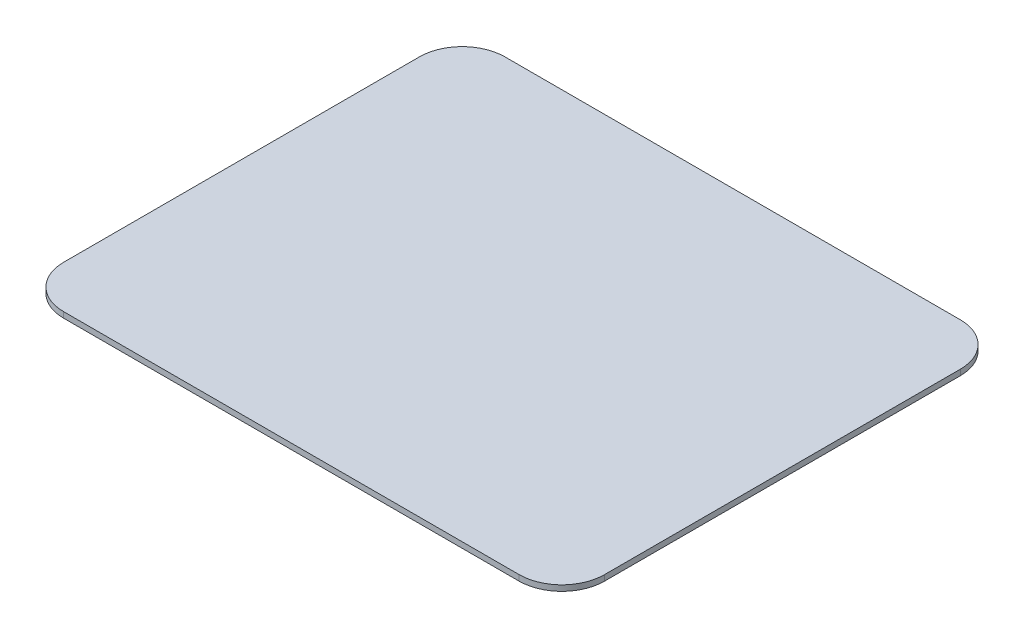
SolidWorks part; units mm, degrees
ref_plane "Front Plane" through (0, 0, 0) normal (0, 0, 1) x (1, 0, 0)
ref_plane "Top Plane" through (0, 0, 0) normal (0, 1, 0) x (1, 0, 0)
ref_plane "Right Plane" through (0, 0, 0) normal (1, 0, 0) x (0, 0, -1)
sketch "Sketch1" plane through (0, 0, 0) normal (0, 1, 0) x (1, 0, 0)
  line L1 (160, -155) -> (-160, -155)
  line L2 (190, -125) -> (190, 125)
  line L3 (160, 155) -> (-160, 155)
  line L4 (-190, -125) -> (-190, 125)
  line L5 (190, -155) -> (-190, 155) construction
  line L6 (190, 155) -> (-190, -155) construction
  arc A0 (-190, 125) -> (-160, 155) centre (-160, 125) cw
  arc A1 (190, 125) -> (160, 155) centre (160, 125) ccw
  arc A2 (190, -125) -> (160, -155) centre (160, -125) cw
  arc A3 (-160, -155) -> (-190, -125) centre (-160, -125) cw
  point P0 (0, 0)
  dimension "D3" = 30
  dimension "D4" = 30
  dimension "D1" = 380
  dimension "D2" = 310
extrude "Boss-Extrude1" add sketch "Sketch1" along normal blind 4
